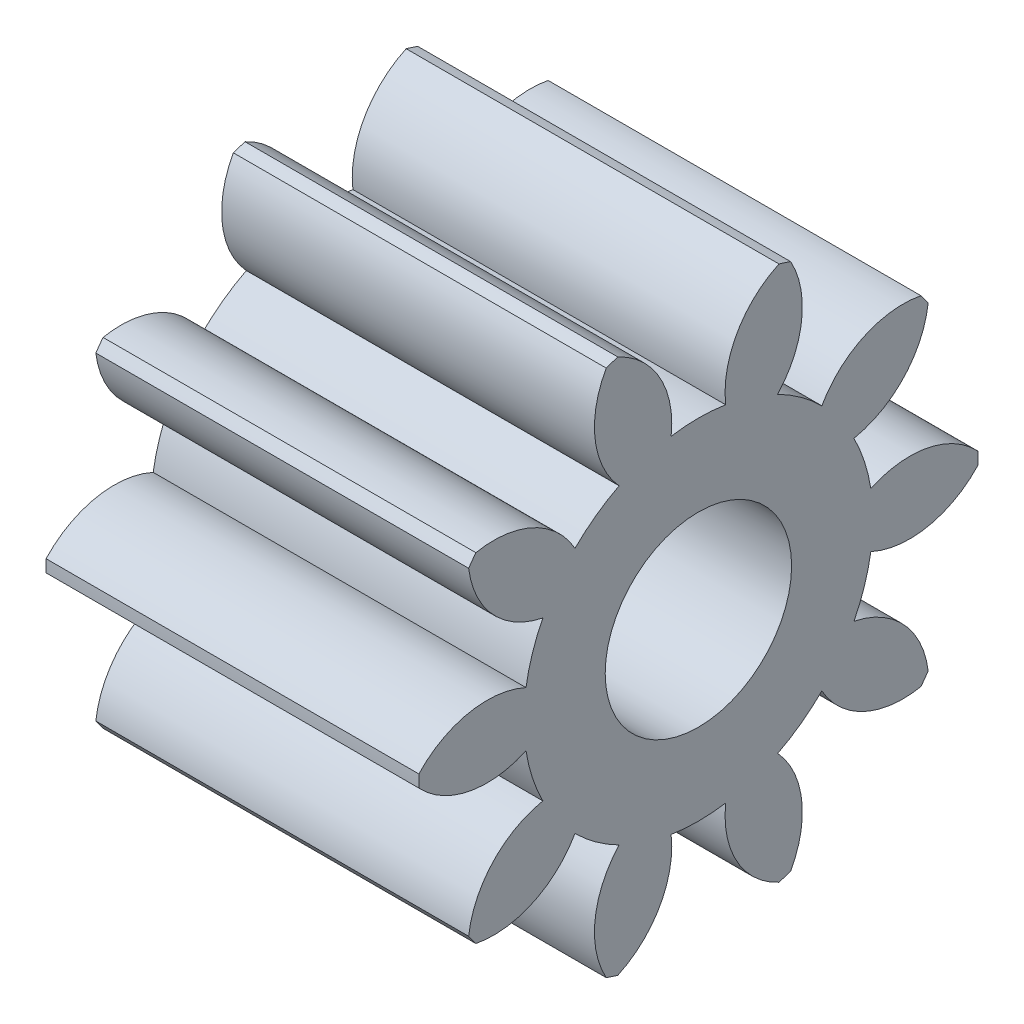
SolidWorks part; units mm, degrees
material "ABS"
ref_plane "Plane1" through (0, 0, 0) normal (0, 0, 1) x (1, 0, 0)
ref_plane "Plane2" through (0, 0, 0) normal (0, 1, 0) x (1, 0, 0)
ref_plane "Plane3" through (0, 0, 0) normal (1, 0, 0) x (0, 0, -1)
sketch "HoldingSke" plane through (0, 0, 0) normal (0, 1, 0) x (1, 0, 0)
  line L0 (0, 0) -> (3.9392, -0.6946)
  line L1 (-15, 0) -> (100, 0) construction
  line L2 (0, 0) -> (-2.1039, 2.3779)
  line L3 (0, 0) -> (-11.863, 4.5341)
  line L4 (0, 0) -> (8.5048, 1.4996)
  line L5 (0, 0) -> (-46.8476, -17.4728)
  line L6 (0, 0) -> (-1.6579, -1.1186)
  line L7 (-2.1039, 2.3779) -> (8.6586, 51.2059)
  line L8 (-76.2, 54.61) -> (-76.1, 54.61)
  line L9 (-71.009, 38.7566) -> (-53.1078, 45.2721)
  line L10 (-76.2, 71.12) -> (104.1128, 71.12)
  line L11 (0, 0) -> (-2, 0)
  line L12 (-76.2, 101.6) -> (-76.192, 101.6)
  line L13 (24.9733, 27.94) -> (52.9518, 28.4284)
  line L14 (24.9733, 27.94) -> (24.9743, 27.94)
  line L15 (24.9733, 27.94) -> (100.4006, 29.5858)
  line L16 (-63.627, -0.25) -> (-12.827, -0.25)
  circle A0 centre (0, 0) radius 0.5
  circle A1 centre (0, 0) radius 0.9365
  circle A2 centre (0, 0) radius 37.5
  circle A3 centre (0, 0) radius 0.5
  dimension "MHD" = 1.873
  dimension "Hub_dia" = 75
  dimension "Bore" = 1
  dimension "MBD" = 1
  dimension "Num_teeth" = 10
  dimension "Pitch" = 4
  dimension "Overall_len" = 50
  dimension "Show_teeth" = 10
  dimension "Thickness" = 2
  dimension "OAL" = 50.0001
  dimension "T_dim" = 0.1
  dimension "Ap" = 20
  dimension "H" = 19.05
  dimension "Pitch_radius" = 180.3128
  dimension "Width" = 2
  dimension "Backlash" = 0.008
  dimension "Addendum_fac" = 1
  dimension "Dedendum_fac" = 1.25
  dimension "Clearance_fac" = 0.25
  dimension "Dedendum_add" = 0.001
  dimension "Module" = 0.25
sketch "BasProSke" plane through (0, 0, 0) normal (0, 1, 0) x (1, 0, 0)
  line L0 (-10, 0) -> (60, 0) construction
  line L1 (0, 0) -> (0, 1.5)
  line L2 (0, 0) -> (2, 0)
  line L3 (2, 0) -> (2, 1.5)
  line L4 (2, 1.5) -> (0, 1.5)
  dimension "Thickness" = 2
  dimension "Diameter" = 3
revolve "Base-Revolve" add sketch "BasProSke" angle 360 about L0
sketch "TooCutSke" plane through (0, 0, 0) normal (1, 0, 0) x (0, 0, -1)
  line L1 (0, 0) -> (0, 107) construction
  line L2 (0, 0) -> (-0.2095, 1.2323) construction
  line L3 (0, 0) -> (-0.7644, 2.3524) construction
  line L4 (-0.2095, 1.2323) -> (-0.3822, 1.1762) construction
  arc A0 (0.1463, 0.925) -> (-0.1463, 0.925) centre (0, 0) ccw
  arc A1 (0.4686, 1.4516) -> (-0.4686, 1.4516) centre (0, 0) ccw
  circle A2 centre (0, 0) radius 1.25 construction
  circle A3 centre (0, 0) radius 1.1746 construction
  arc A4 (-0.1463, 0.925) -> (-0.4686, 1.4516) centre (-0.6429, 0.983) ccw
  arc A5 (0.4686, 1.4516) -> (0.1463, 0.925) centre (0.6429, 0.983) ccw
  dimension "Root_dia" = 1.873
  dimension "Overcut_dia" = 3.0508
  dimension "Pitch_dia" = 2.5
  dimension "Base_dia" = 2.3492
  dimension "Flank_rad" = 0.5
  dimension "Half_ang" = 18
  dimension "Half_CT" = 0.1815
extrude "ToothCut" cut sketch "TooCutSke" along normal through all
fillet "Breaks" [suppressed] radius 0.005
fillet "RootFillets" [suppressed] radius 0.0635
pattern_circular "TeethCuts" count 10 every 36 about axis through (-10, 0, 0) along (1, 0, 0) of "ToothCut", "RootFillets", "Breaks"
sketch "HubNeaOneSke" plane through (0, 0, 0) normal (-1, 0, 0) x (0, 0, 1)
  circle A0 centre (0, 0) radius 0.9365
  dimension "Diameter" = 1.873
extrude "HubNearOne" [suppressed] add sketch "HubNeaOneSke" along normal blind 48.0001
sketch "HubNeaBotSke" plane through (0, 0, 0) normal (-1, 0, 0) x (0, 0, 1)
  circle A0 centre (0, 0) radius 0.9365
  dimension "Diameter" = 1.873
extrude "HubNearBoth" [suppressed] add sketch "HubNeaBotSke" along normal blind 24
ref_plane "FarPln" through (2, 0, 0) normal (1, 0, 0) x (0, 0, -1)
sketch "HubFarSke" plane through (2, 0, 0) normal (1, 0, 0) x (0, 0, -1)
  circle A0 centre (0, 0) radius 0.9365
  dimension "Diameter" = 1.873
extrude "HubFar" [suppressed] add sketch "HubFarSke" along normal blind 24
sketch "BorSke" plane through (0, 0, 0) normal (1, 0, 0) x (0, 0, -1)
  circle A0 centre (0, 0) radius 0.5
  dimension "Diameter" = 1
extrude "Bore" cut sketch "BorSke" along normal mid plane 100.0001
sketch "KeySke" plane through (0, 0, 0) normal (1, 0, 0) x (0, 0, -1)
  line L0 (-0.05, 0) -> (-0.05, 0.6)
  line L1 (-0.05, 0.6) -> (0.05, 0.6)
  line L2 (0.05, 0.6) -> (0.05, 0)
  line L3 (0, 0) -> (0, 34) construction
  line L4 (-0.05, 0) -> (0.05, 0)
  dimension "Offset" = 0.6
  dimension "Width" = 0.1
extrude "Keyway" [suppressed] cut sketch "KeySke" along normal mid plane 100.0001
pattern_circular "Keyway2" [suppressed] count 2 every 90 about axis through (-10, 0, 0) along (1, 0, 0)
equation "' \"Module@HoldingSke\" = 6.35"
equation "' \"Num_teeth@HoldingSke\" = 12"
equation "' \"Ap@HoldingSke\" =  20"
equation "' \"Ap@HoldingSke\" = 20"
equation "' \"Width@HoldingSke\" = 0.5 * 25.4"
equation "' \"Hub_dia@HoldingSke\"= 1 * 25.4"
equation "' \"Hub_dia@HoldingSke\" = 1 * 25.4"
equation "' \"Overall_len@HoldingSke\" = 1.0 * 25.4"
equation "' \"Bore@HoldingSke\" = 0.75 * 25.4"
equation "' \"T_dim@HoldingSke\" = 0.1 * 25.4"
equation "' \"Width@KeySke\" = 0.25 * 25.4"
equation "' \"Show_teeth@HoldingSke\" = 13"
equation "' \"Backlash@HoldingSke\" = 0.009 * 25.4"
equation "' \"Addendum_fac@HoldingSke\" = 1.0"
equation "' \"Dedendum_fac@HoldingSke\" = 1.25"
equation "' \"Dedendum_add@HoldingSke\" = 0.00005 * 25.4"
equation "' \"Clearance_fac@HoldingSke\" = 0.25"
equation "\"Pitch@HoldingSke\" = 1 / \"Module@HoldingSke\""
equation "\"Overcut_dia@TooCutSke\" = (\"Num_teeth@HoldingSke\" + 2 * \"Addendum_fac@HoldingSke\") / \"Pitch@HoldingSke\" + 0.002 * 25.4"
equation "\"Pitch_dia@TooCutSke\" = \"Num_teeth@HoldingSke\" / \"Pitch@HoldingSke\""
equation "\"Base_dia@TooCutSke\" = \"Num_teeth@HoldingSke\" / \"Pitch@HoldingSke\" * cos((\"Ap@HoldingSke\"  * 3.14159265 / 180))"
equation "\"Root_dia@TooCutSke\" = (\"Num_teeth@HoldingSke\" + 2) / \"Pitch@HoldingSke\" - 2 * (\"Addendum_fac@HoldingSke\" + \"Dedendum_fac@HoldingSke\") / \"Pitch@HoldingSke\" - \"Dedendum_add@HoldingSke\" * 2"
equation "\"Half_ang@TooCutSke\" = 180 / \"Num_teeth@HoldingSke\""
equation "\"Half_CT@TooCutSke\" = \"Num_teeth@HoldingSke\" / \"Pitch@HoldingSke\" * sin((3.14159265 / 2 / \"Num_teeth@HoldingSke\")) / 2 - 7 * \"Backlash@HoldingSke\" / 4"
equation "\"Flank_rad@TooCutSke\" = \"Num_teeth@HoldingSke\" / \"Pitch@HoldingSke\" / 5"
equation "\"Radius@RootFillets\" = \"Clearance_fac@HoldingSke\" / \"Pitch@HoldingSke\" + \"Dedendum_add@HoldingSke\""
equation "\"Break_rad@Breaks\" = 0.02 / \"Pitch@HoldingSke\""
equation "\"Thickness@HoldingSke\" = \"Width@HoldingSke\""
equation "\"OAL@HoldingSke\" = \"Thickness@HoldingSke\""
equation "\"MHD@HoldingSke\" = (\"Num_teeth@HoldingSke\" + 2) / \"Pitch@HoldingSke\" - 2 * (\"Addendum_fac@HoldingSke\" + \"Dedendum_fac@HoldingSke\")  / \"Pitch@HoldingSke\" - \"Dedendum_add@HoldingSke\" * 2"
equation "\"MBD@HoldingSke\" = (\"Num_teeth@HoldingSke\" + 2) / \"Pitch@HoldingSke\" - 2 * (\"Addendum_fac@HoldingSke\" + \"Dedendum_fac@HoldingSke\")  / \"Pitch@HoldingSke\" - \"Dedendum_add@HoldingSke\" * 2 - 0.002 * 25.4"
equation "\"MHD@HoldingSke\" = ((sgn( \"MHD@HoldingSke\" - \"Hub_dia@HoldingSke\" )-1)*( \"MHD@HoldingSke\" - \"Hub_dia@HoldingSke\" ))/-2+ \"Hub_dia@HoldingSke\""
equation "\"MBD@HoldingSke\" = ((sgn( \"MBD@HoldingSke\" - \"Bore@HoldingSke\" )-1)*( \"MBD@HoldingSke\" - \"Bore@HoldingSke\" ))/-2+ \"Bore@HoldingSke\""
equation "\"OAL@HoldingSke\" = ((sgn( \"OAL@HoldingSke\" - \"Overall_len@HoldingSke\" )+1)*( \"OAL@HoldingSke\" - \"Overall_len@HoldingSke\" ))/2 + \"Overall_len@HoldingSke\" + 0.000002 * 25.4"
equation "\"Num_teeth@TeethCuts\" = int( \"Show_teeth@HoldingSke\" ) + 1"
equation "\"Num_teeth@TeethCuts\" = ((sgn( \"Num_teeth@TeethCuts\" - \"Num_teeth@HoldingSke\" )-1)*( \"Num_teeth@TeethCuts\" - \"Num_teeth@HoldingSke\" ))/-2+ \"Num_teeth@HoldingSke\""
equation "\"Num_teeth@TeethCuts\" = ((sgn( \"Num_teeth@TeethCuts\" - 2.0)+1)*( \"Num_teeth@TeethCuts\" - 2.0))/2 +2.0"
equation "\"Angle@TeethCuts\" = 360.0 / \"Num_teeth@HoldingSke\""
equation "\"Diameter@BasProSke\" = (\"Num_teeth@HoldingSke\" + 2 * \"Addendum_fac@HoldingSke\") / \"Pitch@HoldingSke\""
equation "\"Thickness@BasProSke\"  = \"Thickness@HoldingSke\""
equation "' \"Fillet_rad@BasProSke\" =  \"Thickness@HoldingSke\" * 0.05"
equation "' \"Fillet_rad@BasProSke\" = \"Thickness@HoldingSke\" * 0.05"
equation "\"MHD@HoldingSke\" = ((sgn( \"MHD@HoldingSke\" - \"Root_dia@TooCutSke\" )-1)*( \"MHD@HoldingSke\" - \"Root_dia@TooCutSke\" ))/-2+ \"Root_dia@TooCutSke\""
equation "\"Diameter@HubNeaOneSke\" = \"MHD@HoldingSke\""
equation "\"Length@HubNearOne\" = \"OAL@HoldingSke\" - \"Thickness@BasProSke\""
equation "\"Diameter@HubNeaBotSke\" = \"MHD@HoldingSke\""
equation "\"Length@HubNearBoth\" = ( \"OAL@HoldingSke\" - \"Thickness@BasProSke\" ) / 2.0"
equation "\"Thickness@FarPln\" = \"Thickness@BasProSke\""
equation "\"Diameter@HubFarSke\" = \"MHD@HoldingSke\""
equation "\"Length@HubFar\" = ( \"OAL@HoldingSke\" - \"Thickness@BasProSke\" ) / 2.0"
equation "\"Diameter@BorSke\" = \"MBD@HoldingSke\""
equation "\"D1@Bore\" = \"OAL@HoldingSke\" * 2.0"
equation "\"D1@Keyway\" = \"OAL@HoldingSke\" * 2.0"
equation "\"Offset@KeySke\" = \"T_dim@HoldingSke\" + \"MBD@HoldingSke\" / 2.0"
